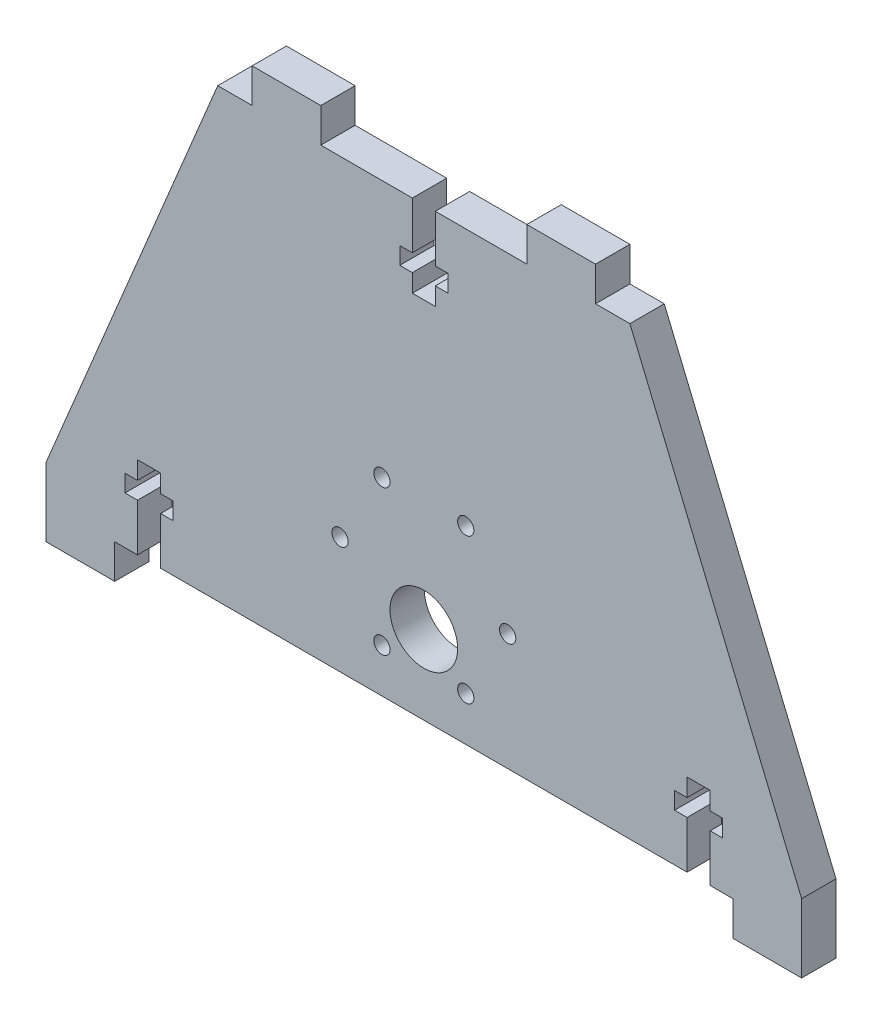
SolidWorks part; units mm, degrees
ref_plane "Front Plane" through (0, 0, 0) normal (0, 0, 1) x (1, 0, 0)
ref_plane "Top Plane" through (0, 0, 0) normal (0, 1, 0) x (1, 0, 0)
ref_plane "Right Plane" through (0, 0, 0) normal (1, 0, 0) x (0, 0, -1)
sketch "Sketch1" plane through (0, 0, 0) normal (0, 0, 1) x (1, 0, 0)
  line L1 (-69.85, 41.275) -> (69.85, 41.275)
  line L2 (-69.85, 41.275) -> (-69.85, -41.275)
  line L3 (-69.85, -41.275) -> (69.85, -41.275)
  line L4 (69.85, 41.275) -> (69.85, -41.275)
  line L5 (-69.85, 41.275) -> (69.85, -41.275) construction
  line L6 (-69.85, -41.275) -> (69.85, 41.275) construction
  point P0 (0, 0)
  dimension "D1" = 82.55
  dimension "D2" = 139.7
extrude "Boss-Extrude1" add sketch "Sketch1" along normal blind 6.35
sketch "Sketch2" plane through (0, 0, 0) normal (0, 0, -1) x (-1, 0, 0)
  line L0 (69.85, -41.275) -> (-69.85, -41.275) construction
  line L1 (-69.85, -41.275) -> (-57.15, -41.275)
  line L2 (-69.85, -41.275) -> (-69.85, -47.625)
  line L3 (-69.85, -47.625) -> (-57.15, -47.625)
  line L4 (-57.15, -41.275) -> (-57.15, -47.625)
  line L5 (-69.85, -41.275) -> (-69.85, 41.275) construction
  line L6 (-69.85, 41.275) -> (69.85, 41.275) construction
  line L7 (-31.75, 41.275) -> (-19.05, 41.275)
  line L8 (-31.75, 41.275) -> (-31.75, 47.625)
  line L9 (-31.75, 47.625) -> (-19.05, 47.625)
  line L10 (-19.05, 41.275) -> (-19.05, 47.625)
  dimension "D1" = 6.35
  dimension "D2" = 12.7
  dimension "D3" = 0
  dimension "D4" = 6.35
  dimension "D5" = 12.7
  dimension "D6" = 38.1
extrude "Boss-Extrude2" add sketch "Sketch2" against normal blind 6.35
sketch "Sketch3" plane through (0, 0, 0) normal (0, 0, -1) x (-1, 0, 0)
  line L1 (-52.9336, -41.275) -> (-52.9336, -32.512)
  line L2 (69.85, -41.275) -> (-57.15, -41.275) construction
  line L3 (-52.9336, -32.512) -> (-55.245, -32.512)
  line L4 (-55.245, -32.512) -> (-55.245, -29.337)
  line L5 (-55.245, -29.337) -> (-52.9336, -29.337)
  line L6 (-52.9336, -29.337) -> (-52.9336, -26.035)
  line L7 (-52.9336, -26.035) -> (-48.6664, -26.035)
  line L8 (-50.8, -26.035) -> (-50.8, -41.275) construction
  line L9 (-48.6664, -41.275) -> (-52.9336, -41.275)
  line L10 (-69.85, -47.625) -> (-57.15, -47.625) construction
  line L11 (-48.6664, -29.337) -> (-48.6664, -26.035)
  line L12 (-46.355, -29.337) -> (-48.6664, -29.337)
  line L13 (-46.355, -32.512) -> (-46.355, -29.337)
  line L14 (-48.6664, -32.512) -> (-46.355, -32.512)
  line L15 (-48.6664, -41.275) -> (-48.6664, -32.512)
  line L16 (-57.15, -47.625) -> (-57.15, -41.275) construction
  dimension "D1" = 21.59
  dimension "D2" = 3.302
  dimension "D3" = 3.175
  dimension "D4" = 4.2672
  dimension "D5" = 4.445
  dimension "D6" = 6.35
extrude "Cut-Extrude1" cut sketch "Sketch3" against normal blind 6.35
sketch "Sketch7" plane through (0, 0, 0) normal (0, 0, -1) x (-1, 0, 0)
  line L0 (-38.1, 41.275) -> (-69.85, -34.925)
  line L1 (-69.85, 41.275) -> (-31.75, 41.275) construction
  line L2 (-69.85, -47.625) -> (-69.85, 41.275) construction
  line L3 (-69.85, -34.925) -> (-69.85, 41.275)
  line L4 (-69.85, 41.275) -> (-38.1, 41.275)
  line L5 (-31.75, 47.625) -> (-31.75, 41.275) construction
  dimension "D1" = 6.35
  dimension "D2" = 12.7
extrude "Cut-Extrude8" cut sketch "Sketch7" against normal blind 6.35
mirror "Mirror2" about plane through (0, 0, 0) normal (1, 0, 0) of "Cut-Extrude8", "Boss-Extrude2"
mirror "Mirror4" about plane through (0, 0, 0) normal (1, 0, 0) of "Cut-Extrude1"
sketch "Sketch4" plane through (0, 0, 0) normal (0, 0, -1) x (-1, 0, 0)
  line L0 (0, 41.275) -> (0, 0) construction
  line L2 (2.1209, 41.275) -> (-2.1209, 41.275)
  line L3 (-2.1209, 41.275) -> (-2.1209, 32.512)
  line L4 (-2.1209, 32.512) -> (-4.445, 32.512)
  line L5 (-4.445, 32.512) -> (-4.445, 29.337)
  line L6 (-4.445, 29.337) -> (-2.1209, 29.337)
  line L7 (-2.1209, 29.337) -> (-2.1209, 26.035)
  line L8 (-2.1209, 26.035) -> (2.1209, 26.035)
  line L10 (2.1209, 29.337) -> (2.1209, 26.035)
  line L11 (4.445, 29.337) -> (2.1209, 29.337)
  line L12 (4.445, 32.512) -> (4.445, 29.337)
  line L13 (2.1209, 32.512) -> (4.445, 32.512)
  line L14 (2.1209, 41.275) -> (2.1209, 32.512)
  line L15 (-19.05, 47.625) -> (-31.75, 47.625) construction
  line L16 (-19.05, 41.275) -> (19.05, 41.275) construction
  point P15 (0, 26.035)
  dimension "D1" = 2.1209
  dimension "D2" = 4.445
  dimension "D3" = 21.59
  dimension "D4" = 3.302
  dimension "D5" = 3.175
extrude "Cut-Extrude2" cut sketch "Sketch4" against normal blind 6.35
sketch "Sketch5" plane through (0, 0, 0) normal (0, 0, -1) x (-1, 0, 0)
  circle A0 centre (-15.5, -7) radius 1.25 construction
  circle A1 centre (0, -14) radius 6 construction
  circle A2 centre (-7.75, -20.4234) radius 1.25 construction
  circle A3 centre (-7.75, 6.4234) radius 1.25 construction
  circle A4 centre (7.75, 6.4234) radius 1.25 construction
  circle A5 centre (15.5, -7) radius 1.25 construction
  circle A6 centre (7.75, -20.4234) radius 1.25 construction
  circle A7 centre (-15.5, -7) radius 1.25 construction
  circle A8 centre (0, -14) radius 6 construction
  circle A9 centre (-7.75, -20.4234) radius 1.25 construction
  circle A10 centre (-7.75, 6.4234) radius 1.25 construction
  circle A11 centre (7.75, 6.4234) radius 1.25 construction
  circle A12 centre (15.5, -7) radius 1.25 construction
  circle A13 centre (7.75, -20.4234) radius 1.25 construction
  circle A14 centre (-15.5, -7) radius 1.504
  circle A15 centre (0, -14) radius 6.254
  circle A16 centre (-7.75, -20.4234) radius 1.504
  circle A17 centre (-7.75, 6.4234) radius 1.504
  circle A18 centre (7.75, 6.4234) radius 1.504
  circle A19 centre (15.5, -7) radius 1.504
  circle A20 centre (7.75, -20.4234) radius 1.504
  circle A21 centre (-15.5, -19.7) radius 1.504
  circle A22 centre (0, -26.7) radius 6.254
  circle A23 centre (-7.75, -33.1234) radius 1.504
  circle A24 centre (-7.75, -6.2766) radius 1.504
  circle A25 centre (7.75, -6.2766) radius 1.504
  circle A26 centre (15.5, -19.7) radius 1.504
  circle A27 centre (7.75, -33.1234) radius 1.504
  circle A28 centre (-15.5, -19.7) radius 1.25 construction
  circle A29 centre (0, -26.7) radius 6 construction
  circle A30 centre (-7.75, -33.1234) radius 1.25 construction
  circle A31 centre (-7.75, -6.2766) radius 1.25 construction
  circle A32 centre (7.75, -6.2766) radius 1.25 construction
  circle A33 centre (15.5, -19.7) radius 1.25 construction
  circle A34 centre (7.75, -33.1234) radius 1.25 construction
  dimension "D2" = 2
  dimension "D1" = 0.254
extrude "Cut-Extrude9" cut sketch "Sketch5" against normal blind 6.35 contours A22 | A21 | A24 | A25 | A26 | A27 | A23
